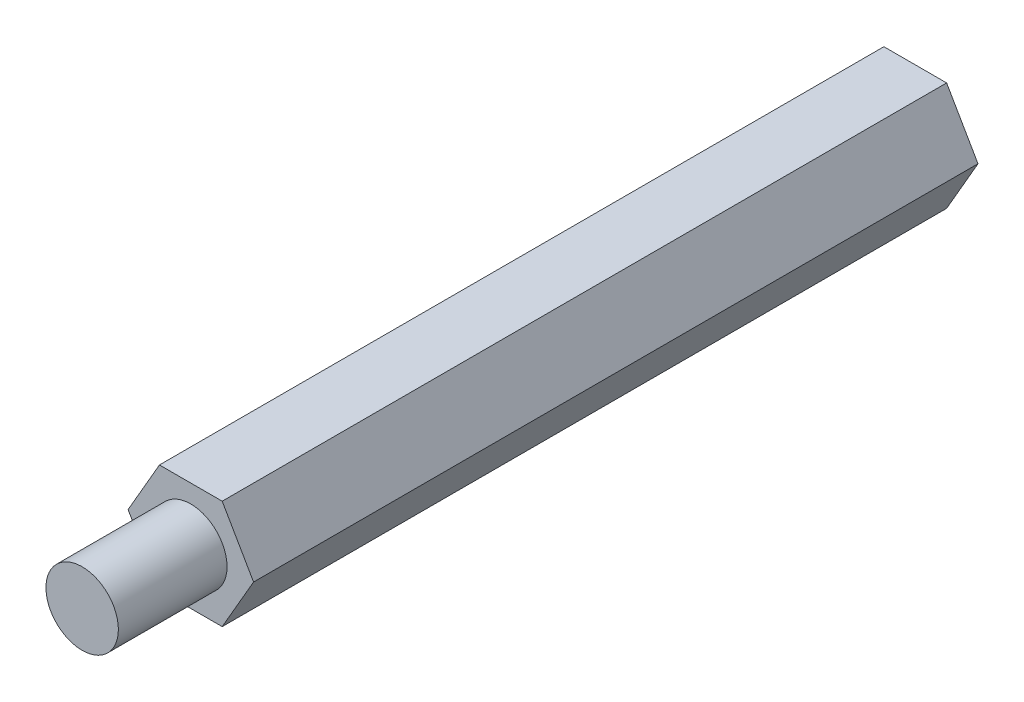
SolidWorks part; units mm, degrees
ref_plane "정면" through (0, 0, 0) normal (0, 0, 1) x (1, 0, 0)
ref_plane "윗면" through (0, 0, 0) normal (0, 1, 0) x (1, 0, 0)
ref_plane "우측면" through (0, 0, 0) normal (1, 0, 0) x (0, 0, -1)
sketch "스케치1" plane through (0, 0, 0) normal (0, 0, 1) x (1, 0, 0)
  line L1 (0.866, -1.5) -> (1.7321, 0)
  line L2 (1.7321, 0) -> (0.866, 1.5)
  line L3 (0.866, 1.5) -> (-0.866, 1.5)
  line L4 (-0.866, 1.5) -> (-1.7321, 0)
  line L5 (-1.7321, 0) -> (-0.866, -1.5)
  line L6 (-0.866, -1.5) -> (0.866, -1.5)
  circle A0 centre (0, 0) radius 1.5 construction
  dimension "D1" = 3
extrude "보스-돌출1" add sketch "스케치1" along normal blind 20
sketch "스케치2" plane through (0, 0, 20) normal (0, 0, 1) x (1, 0, 0)
  circle A0 centre (0, 0) radius 1
  dimension "D1" = 2
extrude "보스-돌출2" add sketch "스케치2" along normal blind 3
sketch "스케치3" plane through (0, 0, 0) normal (0, 0, -1) x (-1, 0, 0)
  point P0 (0, 0)
hole_wizard "M2 여유 구멍1" positions "스케치6" profile "스케치7" hole size "M2" standard "Ansi Metric"
sketch "스케치6" plane through (0, 0, 0) normal (0, 0, -1) x (-1, 0, 0)
  point P0 (0, 0)
sketch "스케치7" plane through (0, 0, 0) normal (1, 0, 0) x (0, 1, 0)
  line L0 (0, 0) -> (0, 3.721)
  line L1 (0, 3.721) -> (1.2, 3)
  line L2 (1.2, 3) -> (1.2, 0)
  line L5 (1.2, 0) -> (0, 0)
  line L10 (0, 3.721) -> (-1.2, 3) construction
  line L11 (0, -6.35) -> (0, 107.95) construction
  dimension "구멍 지름" = 2.4
  dimension "구멍 깊이" = 3
  dimension "드릴 각도" = 118
